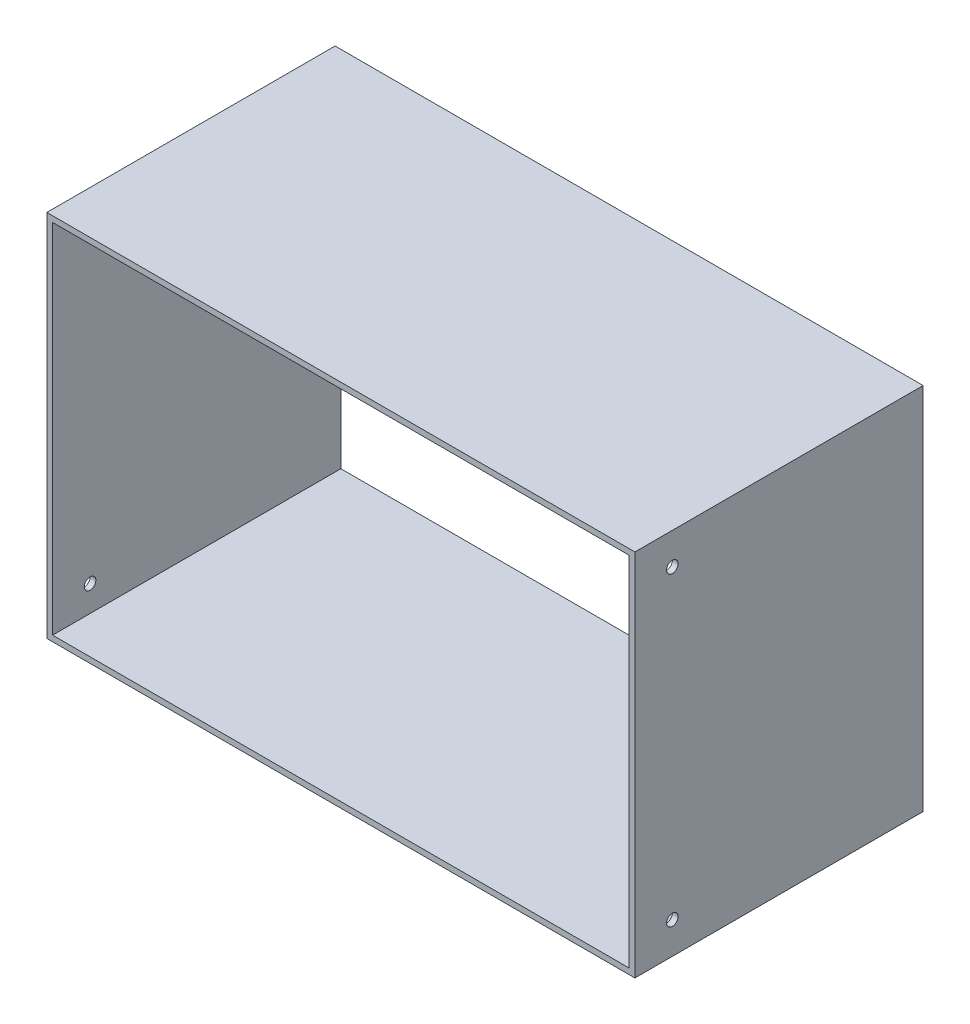
SolidWorks part; units mm, degrees
ref_plane "Спереди" through (0, 0, 0) normal (0, 0, 1) x (1, 0, 0)
ref_plane "Сверху" through (0, 0, 0) normal (0, 1, 0) x (1, 0, 0)
ref_plane "Справа" through (0, 0, 0) normal (1, 0, 0) x (0, 0, -1)
sketch "Эскиз1" plane through (0, 0, 0) normal (0, 0, 1) x (1, 0, 0)
  line L0 (2, 66) -> (2, 2)
  line L1 (2, 2) -> (104, 2)
  line L2 (104, 2) -> (104, 66)
  line L3 (104, 66) -> (2, 66)
  line L13 (3, 65) -> (103, 65)
  line L14 (103, 65) -> (103, 3)
  line L15 (103, 3) -> (3, 3)
  line L16 (3, 3) -> (3, 65)
  dimension "D8" = 1
  dimension "D10" = 1
  dimension "D9" = 1
  dimension "D1" = 64
  dimension "D2" = 102
  dimension "D7" = 1
extrude "Бобышка-Вытянуть1" add sketch "Эскиз1" along normal blind 50
sketch "Эскиз4" plane through (0, 66, 0) normal (0, 1, 0) x (1, 0, 0)
  line L0 (2, 0) -> (2, 1)
  line L1 (2, 0) -> (104, 0)
  line L2 (104, 0) -> (104, 1)
  line L3 (2, 1) -> (104, 1)
sketch "Эскиз5" plane through (103, 0, 0) normal (-1, 0, 0) x (0, 0, 1)
  circle A0 centre (43.5, 7.5) radius 1
  circle A1 centre (43.5, 60.5) radius 1
extrude "Вырез-Вытянуть2" cut sketch "Эскиз5" along normal blind 102 and the other way blind 1
